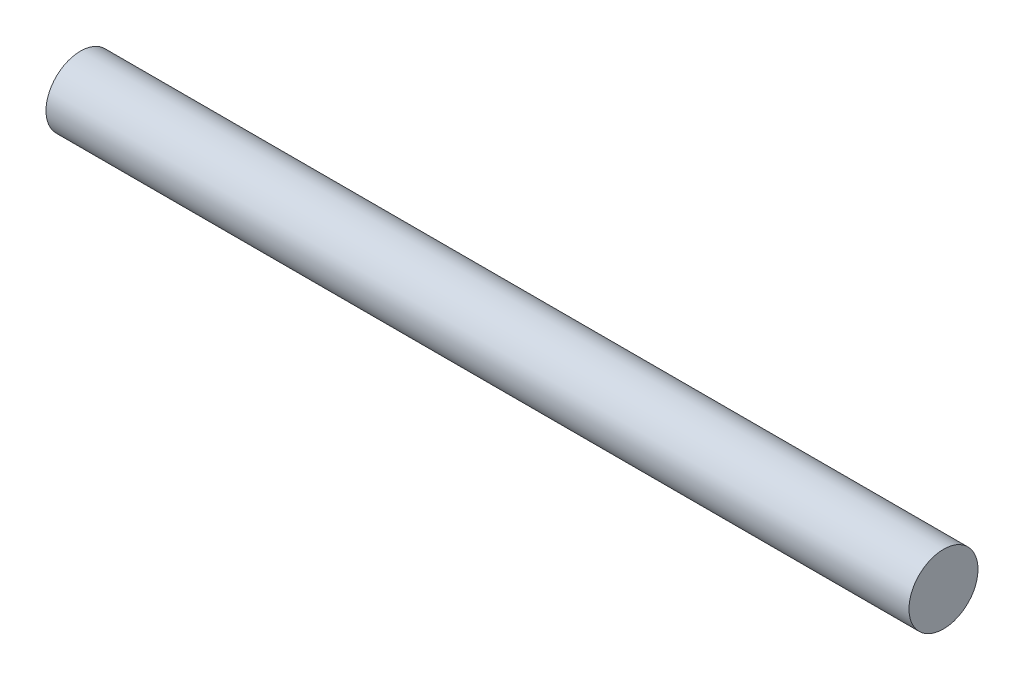
SolidWorks part; units mm, degrees
ref_plane "Front Plane" through (0, 0, 0) normal (0, 0, 1) x (1, 0, 0)
ref_plane "Top Plane" through (0, 0, 0) normal (0, 1, 0) x (1, 0, 0)
ref_plane "Right Plane" through (0, 0, 0) normal (1, 0, 0) x (0, 0, -1)
sketch "Sketch29" plane through (169.9832, 0, 0) normal (1, 0, 0) x (0, 0, -1)
  circle A0 centre (290.5571, 26.9456) radius 4
  dimension "D1" = 8
extrude "Boss-Extrude1" add sketch "Sketch29" along normal blind 100
